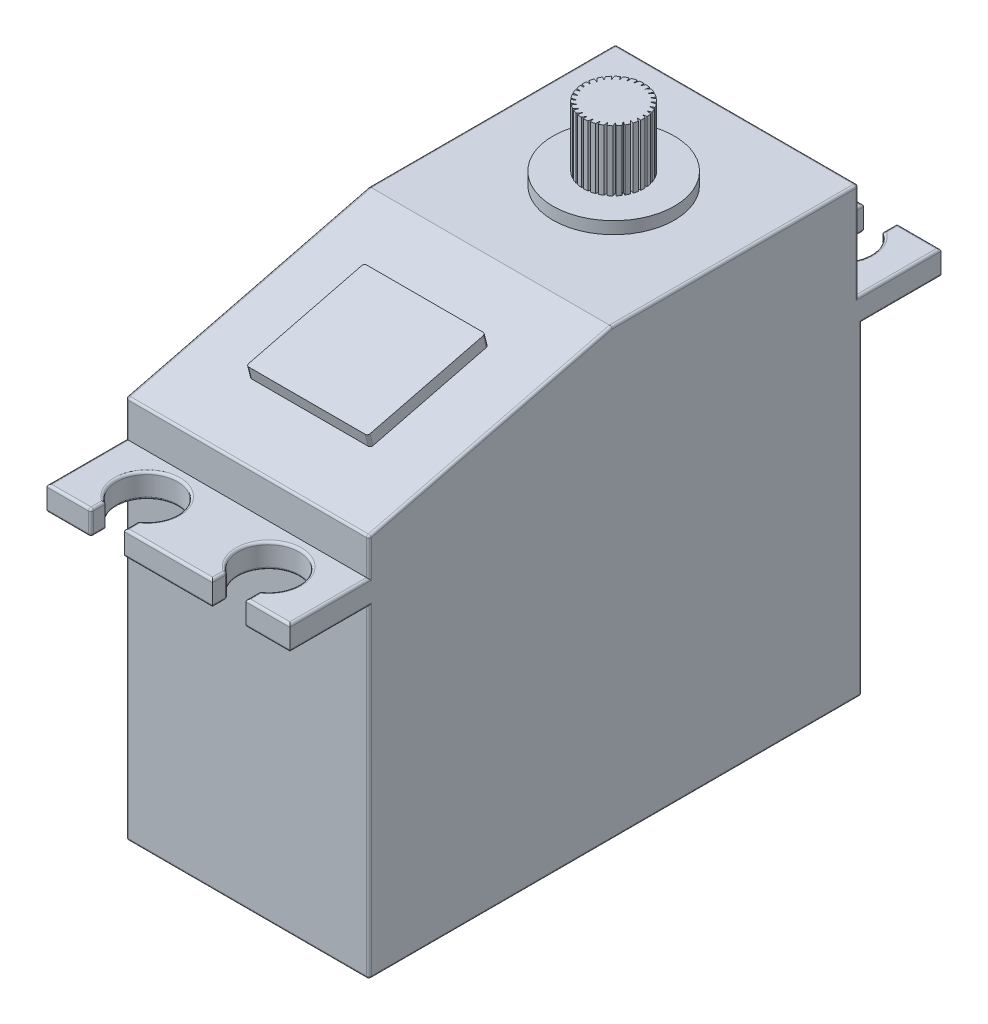
SolidWorks part; units mm, degrees
ref_plane "Front Plane" through (0, 0, 0) normal (0, 0, 1) x (1, 0, 0)
ref_plane "Top Plane" through (0, 0, 0) normal (0, 1, 0) x (1, 0, 0)
ref_plane "Right Plane" through (0, 0, 0) normal (1, 0, 0) x (0, 0, -1)
sketch "Sketch1" plane through (0, 0, 0) normal (1, 0, 0) x (0, 0, -1)
  line L1 (-26.8, 18.3) -> (26.8, 18.3)
  line L2 (-26.8, 18.3) -> (-26.8, -18.3)
  line L3 (-26.8, -18.3) -> (26.8, -18.3)
  line L4 (26.8, 18.3) -> (26.8, -18.3)
  line L5 (-26.8, 18.3) -> (26.8, -18.3) construction
  line L6 (-26.8, -18.3) -> (26.8, 18.3) construction
  point P0 (0, 0)
  dimension "D1" = 36.6
  dimension "D2" = 53.6
extrude "Boss-Extrude1" add sketch "Sketch1" along normal blind 20
sketch "Sketch2" plane through (20, 0, 0) normal (1, 0, 0) x (0, 0, -1)
  line L0 (-26.8, -18.3) -> (26.8, -18.3) construction
  line L1 (-26.8, 8.3) -> (-20.3, 8.3)
  line L2 (-26.8, 8.3) -> (-26.8, -18.3)
  line L3 (-26.8, -18.3) -> (-20.3, -18.3)
  line L4 (-20.3, 8.3) -> (-20.3, -18.3)
  line L5 (-26.8, 8.3) -> (-20.3, -18.3) construction
  line L6 (-26.8, -18.3) -> (-20.3, 8.3) construction
  line L7 (-26.8, 18.3) -> (-26.8, -18.3) construction
  line L8 (0, 11) -> (0, -11) construction
  line L9 (26.8, -18.3) -> (20.3, 8.3) construction
  line L10 (26.8, 8.3) -> (20.3, -18.3) construction
  line L11 (20.3, 8.3) -> (20.3, -18.3)
  line L12 (26.8, -18.3) -> (20.3, -18.3)
  line L13 (26.8, 8.3) -> (26.8, -18.3)
  line L14 (26.8, 8.3) -> (20.3, 8.3)
  line L15 (26.8, -18.3) -> (26.8, 18.3) construction
  line L16 (-26.8, 18.3) -> (-20.3, 18.3)
  line L17 (-26.8, 18.3) -> (-26.8, 10.3)
  line L18 (-26.8, 10.3) -> (-20.3, 10.3)
  line L19 (-20.3, 18.3) -> (-20.3, 10.3)
  line L20 (26.8, 10.3) -> (20, 10.3)
  line L21 (26.8, 10.3) -> (26.8, 18.3)
  line L22 (26.8, 18.3) -> (20, 18.3)
  line L23 (20, 10.3) -> (20, 18.3)
  line L24 (26.8, 18.3) -> (-26.8, 18.3) construction
  point P0 (-23.55, -5)
  point P15 (23.55, -5)
  point P29 (0, 0)
  dimension "D1" = 6.5
  dimension "D2" = 26.6
  dimension "D3" = 6.5
  dimension "D4" = 40.3
  dimension "D5" = 8
extrude "Cut-Extrude1" cut sketch "Sketch2" against normal through all
sketch "Sketch3" plane through (0, 10.3, 0) normal (0, 1, 0) x (1, 0, 0)
  line L1 (0, -26.8) -> (0, -20.3) construction
  line L2 (3.624, -26.8) -> (6.376, -26.8)
  line L3 (0, -26.8) -> (20, -26.8) construction
  line L4 (6.376, -26.8) -> (6.376, -25.6373)
  line L5 (3.624, -26.8) -> (3.624, -25.6373)
  line L6 (10, -26.8) -> (10, -20.3) construction
  line L7 (0, -20.3) -> (20, -20.3) construction
  line L8 (16.376, -26.8) -> (16.376, -25.6373)
  line L9 (13.624, -26.8) -> (13.624, -25.6373)
  line L10 (16.376, -26.8) -> (13.624, -26.8)
  arc A1 (6.376, -25.6373) -> (3.624, -25.6373) centre (5, -23.55) ccw
  arc A2 (13.624, -25.6373) -> (16.376, -25.6373) centre (15, -23.55) cw
  point P13 (5, -26.8)
  dimension "D1" = 5
  dimension "D2" = 2.5
  dimension "D3" = 1.1627
  dimension "D4" = 2.752
extrude "Cut-Extrude2" cut sketch "Sketch3" against normal through all
mirror "Mirror1" about plane through (0, 0, 0) normal (0, 0, 1) of "Cut-Extrude2"
sketch "Sketch4" plane through (20, 0, 0) normal (1, 0, 0) x (0, 0, -1)
  line L0 (-20.3, 10.3) -> (-20.3, 18.3) construction
  line L1 (-20.3, 18.3) -> (-0.3, 18.3)
  line L2 (-20.3, 18.3) -> (-20.3, 13.3)
  line L5 (20, 18.3) -> (-20.3, 18.3) construction
  line L6 (-0.3, 18.3) -> (-20.3, 13.3)
  dimension "D1" = 20
  dimension "D2" = 5
extrude "Cut-Extrude3" cut sketch "Sketch4" against normal through all
sketch "Sketch5" plane through (0, 18.3, 0) normal (0, 1, 0) x (1, 0, 0)
  line L0 (20, 20) -> (20, -0.3) construction
  line L1 (0, 20) -> (20, 20) construction
  circle A0 centre (10, 9.85) radius 5
  point P2 (0, 0)
  point P5 (20, 9.85)
  point P6 (0, 0)
  point P9 (10, 20)
  dimension "D1" = 10
extrude "Boss-Extrude2" add sketch "Sketch5" along normal blind 1
sketch "Sketch6" plane through (0, 19.3, 0) normal (0, 1, 0) x (1, 0, 0)
  circle A0 centre (10, 9.85) radius 2.5
  dimension "D1" = 5
extrude "Boss-Extrude3" add sketch "Sketch6" along normal blind 5
sketch "Sketch7" plane through (0, 24.3, 0) normal (0, 1, 0) x (1, 0, 0)
  line L0 (10, 12.35) -> (10, 12.0144)
  line L1 (10, 12.0144) -> (10.1686, 12.3443)
  circle A0 centre (10, 9.85) radius 2.5 construction
  circle A1 centre (10, 9.85) radius 2.5 construction
  arc A2 (10.1686, 12.3443) -> (10, 12.35) centre (10, 9.85) ccw
  dimension "D1" = 0.3705
  dimension "D2" = 27.068
extrude "Cut-Extrude4" cut sketch "Sketch7" against normal up to surface (5 mm away) up to face at (10, 19.3, -7.35)
pattern_circular "CirPattern1" count 30 over 360 about axis through (10, 0, -9.85) along (0, 1, 0) of "Cut-Extrude4"
sketch "Sketch8" plane through (0, 17.2941, 4.3235) normal (0, 0.9701, 0.2425) x (1, 0, 0)
  line L0 (0, 4.1474) -> (20, 4.1474) construction
  line L1 (5, -1.1604) -> (15, -1.1604)
  line L2 (5, -1.1604) -> (5, -11.1604)
  line L3 (5, -11.1604) -> (15, -11.1604)
  line L4 (15, -1.1604) -> (15, -11.1604)
  line L5 (20, -16.4682) -> (20, 4.1474) construction
  point P4 (10, -1.1604)
  point P7 (10, 4.1474)
  point P8 (15, -6.1604)
  point P11 (20, -6.1604)
  dimension "D1" = 10
  dimension "D2" = 10
extrude "Boss-Extrude4" add sketch "Sketch8" along normal blind 1
fillet "Fillet1" radius 0.2 69 edges at (15, 8.3, 21.05) (13.624, 9.3, 25.6373) (15, 10.3, 21.05) (16.376, 9.3, 25.6373) (0, -18.3, 0) (20, -18.3, 0) (5, 15.0724, 15.272) (15, 15.0724, 15.272) (15, 17.4977, 5.5706) (5, 17.4977, 5.5706) (0, 18.3, -9.85) (20, 18.3, -9.85) (0, 15.8, 10.3) (20, 15.8, 10.3) (10, 13.3, 20.3) (3.624, 10.3, -26.2186) (5, 10.3, -21.05) (6.376, 10.3, -26.2186) (15, 10.3, -21.05) (16.376, 10.3, -26.2186) (13.624, 10.3, -26.2186) (3.624, 10.3, 26.2186) (6.376, 10.3, 26.2186) (13.624, 10.3, 26.2186) (16.376, 10.3, 26.2186) (6.376, 8.3, 26.2186) (3.624, 8.3, 26.2186) (13.624, 8.3, 26.2186) (16.376, 8.3, 26.2186) (20, 14.3, -20) (20, 10.3, -23.4) (0, 14.3, -20) (0, 10.3, -23.4) (10, 18.3, -20) (18.188, 10.3, -26.8) (10, 10.3, -26.8) (1.812, 10.3, -26.8) (0, 10.3, 23.55) (0, 11.8, 20.3) (20, 8.3, -23.55) (20, -5, -20.3) (0, 8.3, -23.55) (0, -5, -20.3) (18.188, 8.3, -26.8) (10, 8.3, -26.8) (1.812, 8.3, -26.8) (10, -18.3, -20.3) (0, 8.3, 23.55) (10, -18.3, 20.3) (5, 8.3, -21.05) (6.376, 8.3, -26.2186) (3.624, 8.3, -26.2186) (16.376, 8.3, -26.2186) (15, 8.3, -21.05) (13.624, 8.3, -26.2186) (1.812, 8.3, 26.8) (1.812, 10.3, 26.8) (3.624, 9.3, 26.8) (5, 8.3, 21.05) (5, 10.3, 21.05) (10, 8.3, 26.8) (10, 10.3, 26.8) (18.188, 8.3, 26.8) (18.188, 10.3, 26.8) (20, 8.3, 23.55) (20, 10.3, 23.55) (20, 11.8, 20.3) (20, -5, 20.3) (0, -5, 20.3)
